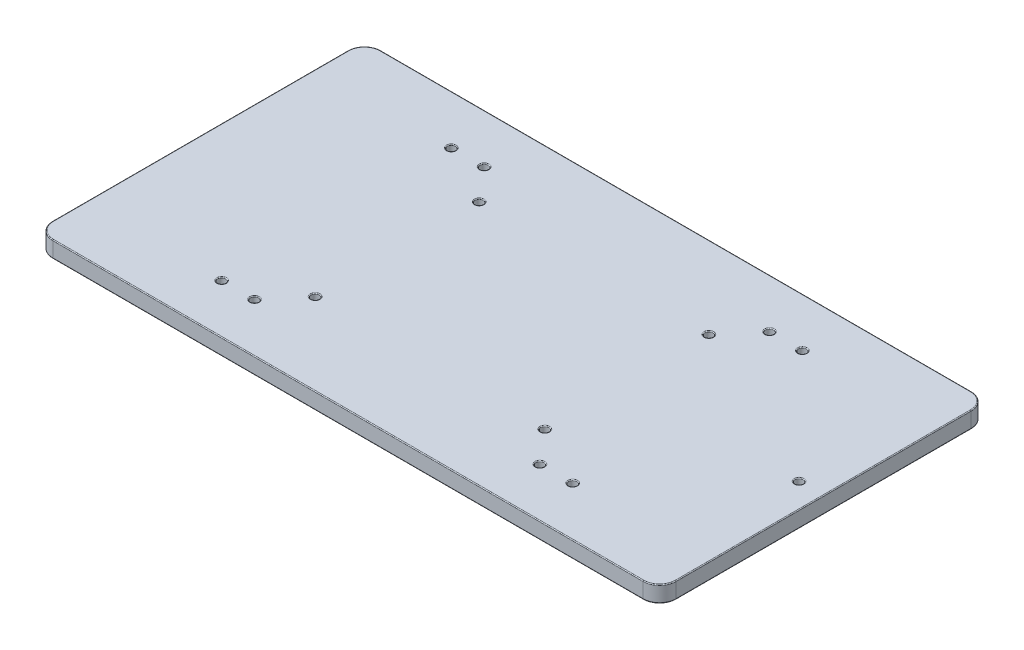
SolidWorks part; units mm, degrees
ref_plane "Front Plane" through (0, 0, 0) normal (0, 0, 1) x (1, 0, 0)
ref_plane "Top Plane" through (0, 0, 0) normal (0, 1, 0) x (1, 0, 0)
ref_plane "Right Plane" through (0, 0, 0) normal (1, 0, 0) x (0, 0, -1)
sketch "Sketch1" plane through (0, 0, 0) normal (0, 1, 0) x (1, 0, 0)
  line L0 (87.5, 50) -> (87.5, -50) construction
  line L1 (-95, 50) -> (95, 50)
  line L2 (-95, 50) -> (-95, -50)
  line L3 (-95, -50) -> (95, -50)
  line L4 (95, 50) -> (95, -50)
  line L5 (-95, 50) -> (95, -50) construction
  line L6 (-95, -50) -> (95, 50) construction
  line L7 (-35, 25) -> (35, 25) construction
  line L8 (-35, 25) -> (-35, -25) construction
  line L9 (-35, -25) -> (35, -25) construction
  line L10 (35, 25) -> (35, -25) construction
  line L11 (-35, 25) -> (35, -25) construction
  line L12 (-35, -25) -> (35, 25) construction
  line L13 (0, 0) -> (23.5476, 0) construction
  line L14 (0, 0) -> (0, 17.3261) construction
  circle A0 centre (-35, 25) radius 1.25
  circle A2 centre (35, -25) radius 1.25
  circle A3 centre (-35, -25) radius 1.25
  circle A4 centre (35, 25) radius 1.25
  circle A5 centre (87.5, 0) radius 1.25
  circle A6 centre (-53.5, -35) radius 1.25
  circle A7 centre (-43.5, -35) radius 1.25
  circle A8 centre (-43.5, 35) radius 1.25
  circle A9 centre (-53.5, 35) radius 1.25
  circle A10 centre (43.5, -35) radius 1.25
  circle A11 centre (53.5, -35) radius 1.25
  circle A12 centre (43.5, 35) radius 1.25
  circle A13 centre (53.5, 35) radius 1.25
  point P0 (0, 0)
  point P6 (0, 0)
  dimension "D5" = 2.5
  dimension "D7" = 2.5
  dimension "D8" = 2.5
  dimension "D1" = 190
  dimension "D2" = 100
  dimension "D3" = 70
  dimension "D4" = 50
  dimension "D6" = 15
  dimension "D9" = 15
  dimension "D10" = 10
  dimension "D11" = 43.5
extrude "Boss-Extrude1" add sketch "Sketch1" along normal blind 5
fillet "Fillet2" radius 5 4 edges at (-95, 2.5, 50) (-95, 2.5, -50) (95, 2.5, -50) (95, 2.5, 50)
fillet "Fillet3" radius 0.25 42 edges at (53.5, 0, -33.75) (53.5, 5, -33.75) (43.5, 0, -33.75) (43.5, 5, -33.75) (53.5, 0, 33.75) (53.5, 5, 33.75) (43.5, 0, 33.75) (43.5, 5, 33.75) (-53.5, 0, -36.25) (-53.5, 5, -36.25) (-43.5, 0, -36.25) (-43.5, 5, -36.25) (-43.5, 0, 36.25) (-43.5, 5, 36.25) (-53.5, 0, 36.25) (-53.5, 5, 36.25) (87.5, 0, 1.25) (87.5, 5, 1.25) (-35, 0, 26.25) (-35, 5, 26.25) (35, 0, 26.25) (35, 5, 26.25) (35, 0, -23.75) (35, 5, -23.75) (-35, 0, -23.75) (-35, 5, -23.75) (95, 0, 0) (0, 0, -50) (-95, 0, 0) (0, 0, 50) (95, 5, 0) (0, 5, -50) (-95, 5, 0) (93.5355, 0, 48.5355) (93.5355, 0, -48.5355) (-93.5355, 0, -48.5355) (-93.5355, 0, 48.5355) (93.5355, 5, 48.5355) (93.5355, 5, -48.5355) (-93.5355, 5, -48.5355) (-93.5355, 5, 48.5355) (0, 5, 50)
